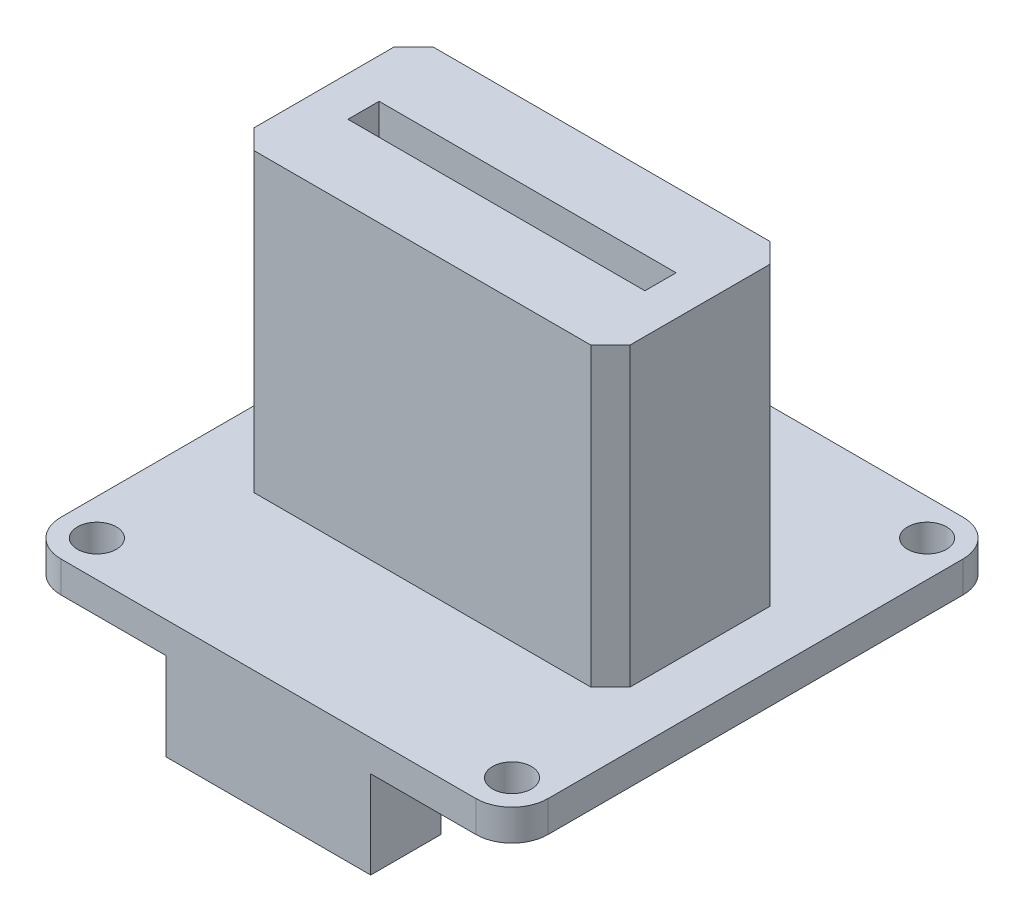
SolidWorks part; units mm, degrees
ref_plane "前视基准面" through (0, 0, 0) normal (0, 0, 1) x (1, 0, 0)
ref_plane "上视基准面" through (0, 0, 0) normal (0, 1, 0) x (1, 0, 0)
ref_plane "右视基准面" through (0, 0, 0) normal (1, 0, 0) x (0, 0, -1)
other "Configuration Table"
sketch "草图2" plane through (0, 0, 0) normal (0, 1, 0) x (1, 0, 0)
  line L1 (-10.65, 12.5) -> (10.65, 12.5)
  line L2 (-12.5, 10.65) -> (-12.5, -10.65)
  line L3 (-10.65, -12.5) -> (10.65, -12.5)
  line L4 (12.5, 10.65) -> (12.5, -10.65)
  line L5 (-12.5, 12.5) -> (12.5, -12.5) construction
  line L6 (-12.5, -12.5) -> (12.5, 12.5) construction
  arc A0 (-10.65, 12.5) -> (-12.5, 10.65) centre (-10.65, 10.65) ccw
  circle A1 centre (-10.65, 10.65) radius 1
  arc A2 (12.5, 10.65) -> (10.65, 12.5) centre (10.65, 10.65) ccw
  circle A3 centre (10.65, 10.65) radius 1
  arc A4 (-12.5, -10.65) -> (-10.65, -12.5) centre (-10.65, -10.65) ccw
  circle A5 centre (-10.65, -10.65) radius 1
  arc A6 (10.65, -12.5) -> (12.5, -10.65) centre (10.65, -10.65) ccw
  circle A7 centre (10.65, -10.65) radius 1
  point P0 (0, 0)
  dimension "D3" = 3.7
  dimension "D4" = 2
  dimension "D5" = 3.7
  dimension "D6" = 2
  dimension "D7" = 3.7
  dimension "D8" = 2
  dimension "D9" = 3.7
  dimension "D10" = 2
  dimension "D1" = 25
  dimension "D2" = 25
  dimension "D11" = 25
  dimension "D12" = 25
  dimension "D13" = 12.5
extrude "凸台-拉伸3" add sketch "草图2" along normal blind 1.6
sketch "草图3" plane through (0, 0, 0) normal (0, 1, 0) x (1, 0, 0)
  line L1 (-9.65, 4.6) -> (9.65, 4.6)
  line L2 (-9.65, 4.6) -> (-9.65, -4.6)
  line L3 (-9.65, -4.6) -> (9.65, -4.6)
  line L4 (9.65, 4.6) -> (9.65, -4.6)
  line L5 (-9.65, 4.6) -> (9.65, -4.6) construction
  line L6 (-9.65, -4.6) -> (9.65, 4.6) construction
  point P0 (0, 0)
  dimension "D1" = 9.2
  dimension "D2" = 19.3
extrude "凸台-拉伸4" add sketch "草图3" along normal blind 15.2 from surface at 1.6 starting at face at (-10.65, 1.6, 11.65)
sketch "草图4" plane through (0, 0, 0) normal (0, 1, 0) x (1, 0, 0)
  line L1 (-7.62, 0.8) -> (7.62, 0.8)
  line L2 (-7.62, 0.8) -> (-7.62, -0.8)
  line L3 (-7.62, -0.8) -> (7.62, -0.8)
  line L4 (7.62, 0.8) -> (7.62, -0.8)
  line L5 (-7.62, 0.8) -> (7.62, -0.8) construction
  line L6 (-7.62, -0.8) -> (7.62, 0.8) construction
  point P0 (0, 0)
  dimension "D1" = 1.6
  dimension "D2" = 15.24
extrude "切除-拉伸1" cut sketch "草图4" against normal blind 9 from surface at 16.8 starting at face at (0, 16.8, 0)
sketch "草图5" plane through (0, 0, 0) normal (0, 1, 0) x (1, 0, 0)
  line L0 (9.65, 4.6) -> (9.65, 3.6)
  line L1 (9.65, 4.6) -> (9.65, -4.6) construction
  line L2 (9.65, 3.6) -> (8.65, 4.6)
  line L3 (-9.65, 4.6) -> (9.65, 4.6) construction
  line L4 (8.65, 4.6) -> (9.65, 4.6)
  line L5 (9.65, -4.6) -> (9.65, -3.6)
  line L6 (9.65, -3.6) -> (8.65, -4.6)
  line L7 (9.65, -4.6) -> (-9.65, -4.6) construction
  line L8 (8.65, -4.6) -> (9.65, -4.6)
  line L9 (-9.65, -4.6) -> (-8.65, -4.6)
  line L10 (9.65, -4.6) -> (-9.65, -4.6) construction
  line L11 (-8.65, -4.6) -> (-9.65, -3.6)
  line L12 (-9.65, -4.6) -> (-9.65, 4.6) construction
  line L13 (-9.65, -3.6) -> (-9.65, -4.6)
  line L14 (-9.65, 4.6) -> (-8.65, 4.6)
  line L15 (-8.65, 4.6) -> (-9.65, 3.6)
  line L16 (-9.65, 3.6) -> (-9.65, 4.6)
  dimension "D1" = 1
  dimension "D2" = 1
  dimension "D3" = 1
  dimension "D4" = 1
  dimension "D5" = 1
  dimension "D6" = 1
  dimension "D7" = 1
  dimension "D8" = 1
extrude "切除-拉伸2" cut sketch "草图5" against normal up to surface (15.2 mm away) from surface at 16.8 up to face at (0, 1.6, 0) starting at face at (0, 16.8, 0)
sketch "草图6" plane through (0, 0, 0) normal (0, 1, 0) x (1, 0, 0)
  line L0 (-10.65, -12.5) -> (10.65, -12.5) construction
  line L1 (-5.25, -12.5) -> (5.25, -12.5)
  line L2 (-5.25, -12.5) -> (-5.25, -8.9)
  line L3 (-5.25, -8.9) -> (5.25, -8.9)
  line L4 (5.25, -12.5) -> (5.25, -8.9)
  line L5 (10.65, 12.5) -> (-10.65, 12.5) construction
  line L6 (-7.5, 8.9) -> (7.5, 8.9)
  line L7 (-7.5, 8.9) -> (-7.5, 12.5)
  line L8 (-7.5, 12.5) -> (7.5, 12.5)
  line L9 (7.5, 8.9) -> (7.5, 12.5)
  point P6 (0, -8.9)
  point P14 (0, 8.9)
  dimension "D1" = 10.5
  dimension "D2" = 3.6
  dimension "D3" = 0
  dimension "D4" = 3.6
  dimension "D5" = 15
  dimension "D6" = 0
extrude "凸台-拉伸5" add sketch "草图6" against normal blind 4.5
